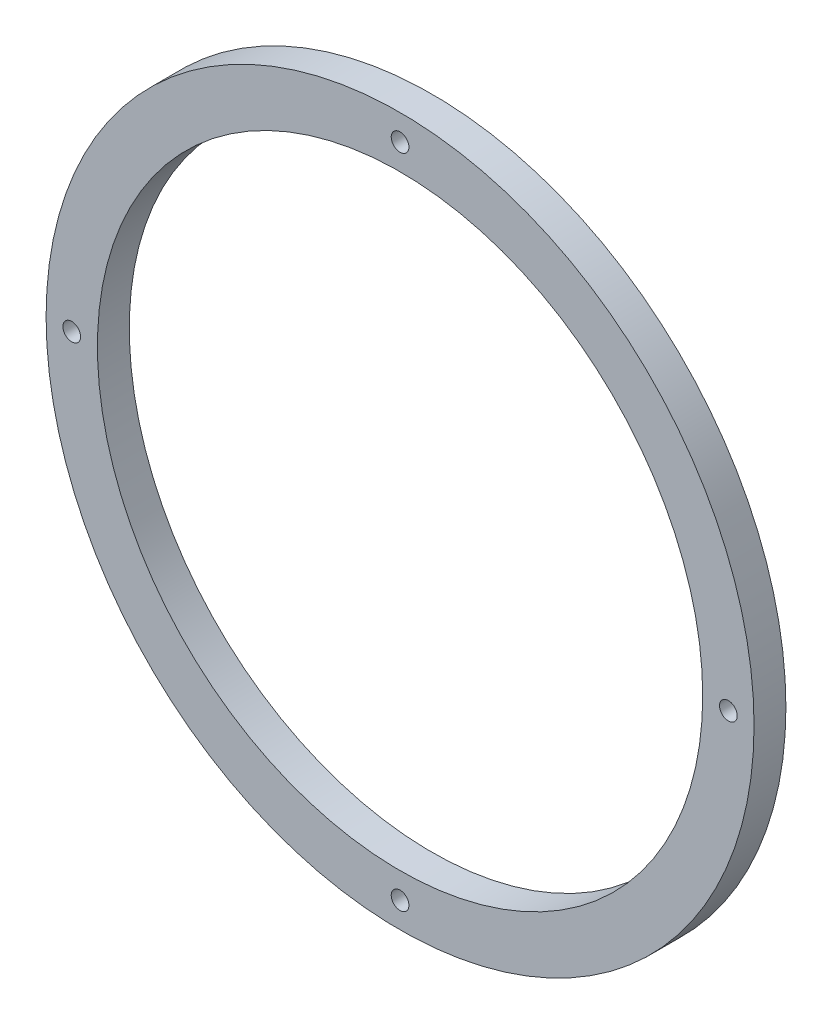
SolidWorks part; units mm, degrees
material "1060 合金"
ref_plane "前视基准面" through (0, 0, 0) normal (0, 0, 1) x (1, 0, 0)
ref_plane "上视基准面" through (0, 0, 0) normal (0, 1, 0) x (1, 0, 0)
ref_plane "右视基准面" through (0, 0, 0) normal (1, 0, 0) x (0, 0, -1)
sketch "草图1" plane through (0, 0, 0) normal (0, 0, 1) x (1, 0, 0)
  circle A0 centre (0, 0) radius 85.5
  circle A1 centre (0, 0) radius 100
  dimension "D1" = 171
  dimension "D2" = 200
extrude "凸台-拉伸1" add sketch "草图1" along normal blind 9
sketch "草图2" plane through (0, 0, 9) normal (0, 0, 1) x (1, 0, 0)
  circle A0 centre (0, 92.75) radius 2.5
  circle A1 centre (92.75, 0) radius 2.5
  circle A2 centre (0, -92.75) radius 2.5
  circle A3 centre (-92.75, 0) radius 2.5
  dimension "D2" = 5
  dimension "D1" = 92.75
  dimension "D3" = 4
extrude "切除-拉伸1" cut sketch "草图2" against normal through all
